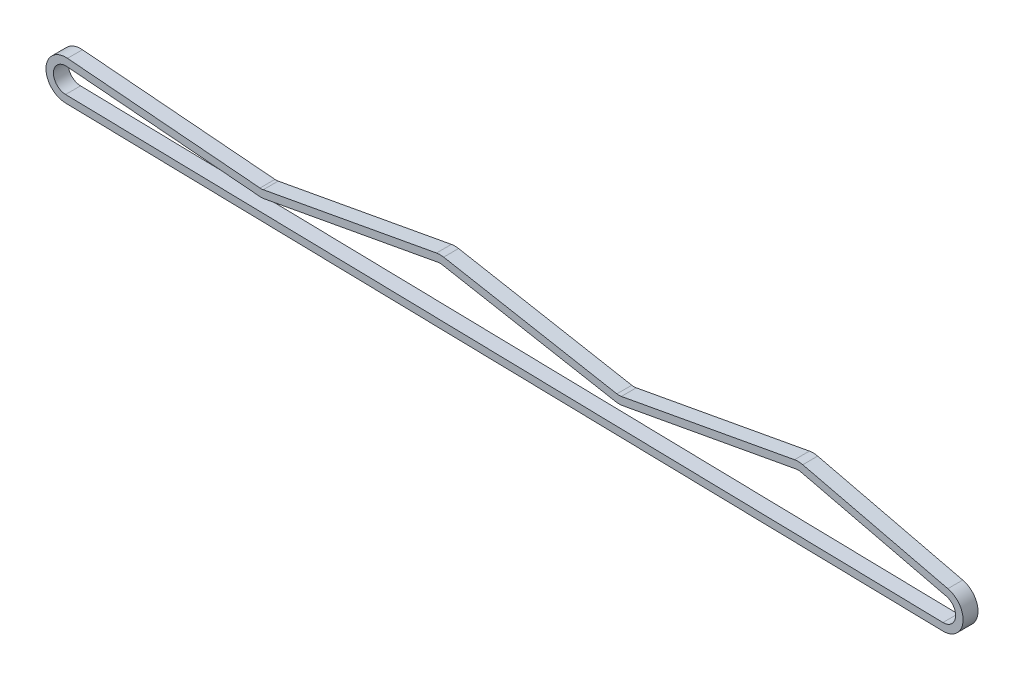
SolidWorks part; units mm, degrees
ref_plane "Front Plane" through (0, 0, 0) normal (0, 0, 1) x (1, 0, 0)
ref_plane "Top Plane" through (0, 0, 0) normal (0, 1, 0) x (1, 0, 0)
ref_plane "Right Plane" through (0, 0, 0) normal (1, 0, 0) x (0, 0, -1)
sketch "Sketch1" plane through (0, 0, 0) normal (0, 0, 1) x (1, 0, 0)
  line L15 (157.2019, -12.9982) -> (-195.6419, -5.4982)
  line L16 (-194.8072, 10.4723) -> (-117.3873, 4.0173)
  line L17 (-116.0691, 4.0822) -> (-46.4163, 16.8685)
  line L18 (-43.5275, 16.8685) -> (26.1253, 4.0822)
  line L19 (27.9309, 4.0822) -> (97.5837, 16.8685)
  line L20 (100.8948, 16.7792) -> (159.2386, 2.7792)
  line L21 (-195.0565, 7.4827) -> (-117.6366, 1.0277)
  line L22 (-115.5275, 1.1315) -> (-45.8747, 13.9178)
  line L23 (-44.0691, 13.9178) -> (25.5837, 1.1315)
  line L24 (28.4725, 1.1315) -> (98.1253, 13.9178)
  line L25 (100.1948, 13.862) -> (158.5386, -0.138)
  line L26 (157.2656, -9.9989) -> (-195.5782, -2.4989)
  circle A0 centre (157.3719, -5) radius 5 construction
  circle A2 centre (99.0281, 9) radius 5 construction
  circle A3 centre (27.0281, 9) radius 5 construction
  circle A4 centre (-44.9719, 9) radius 5 construction
  circle A5 centre (-116.9719, 9) radius 5 construction
  circle A6 centre (-195.4719, 2.5) radius 5 construction
  circle A7 centre (157.3719, -5) radius 5 construction
  circle A9 centre (99.0281, 9) radius 5 construction
  circle A10 centre (27.0281, 9) radius 5 construction
  circle A11 centre (-44.9719, 9) radius 5 construction
  circle A12 centre (-116.9719, 9) radius 5 construction
  circle A13 centre (-195.4719, 2.5) radius 5 construction
  arc A25 (-194.8072, 10.4723) -> (-195.6419, -5.4982) centre (-195.4719, 2.5) ccw
  arc A26 (-117.3873, 4.0173) -> (-116.0691, 4.0822) centre (-116.9719, 9) ccw
  arc A27 (-46.4163, 16.8685) -> (-43.5275, 16.8685) centre (-44.9719, 9) cw
  arc A28 (26.1253, 4.0822) -> (27.9309, 4.0822) centre (27.0281, 9) ccw
  arc A29 (97.5837, 16.8685) -> (100.8948, 16.7792) centre (99.0281, 9) cw
  arc A30 (159.2386, 2.7792) -> (157.2019, -12.9982) centre (157.3719, -5) cw
  arc A31 (-117.6366, 1.0277) -> (-115.5275, 1.1315) centre (-116.9719, 9) ccw
  arc A32 (-45.8747, 13.9178) -> (-44.0691, 13.9178) centre (-44.9719, 9) cw
  arc A33 (25.5837, 1.1315) -> (28.4725, 1.1315) centre (27.0281, 9) ccw
  arc A34 (98.1253, 13.9178) -> (100.1948, 13.862) centre (99.0281, 9) cw
  arc A35 (158.5386, -0.138) -> (157.2656, -9.9989) centre (157.3719, -5) cw
  arc A36 (-195.0565, 7.4827) -> (-195.5782, -2.4989) centre (-195.4719, 2.5) ccw
  point P0 (28.0936, 2.0889)
  point P8 (-113.9677, 5.7093)
  point P10 (159.9806, -9.6681)
  point P37 (-115.5275, 1.0277)
  point P54 (-195.291, 10.6976)
  point P55 (0, 0)
  point P56 (-43.777, 15.9147)
  point P57 (0, 0)
  point P58 (0, 0)
  point P59 (0, 0)
  dimension "D1" = 3
extrude "Boss-Extrude1" add sketch "Sketch1" along normal mid plane 6
